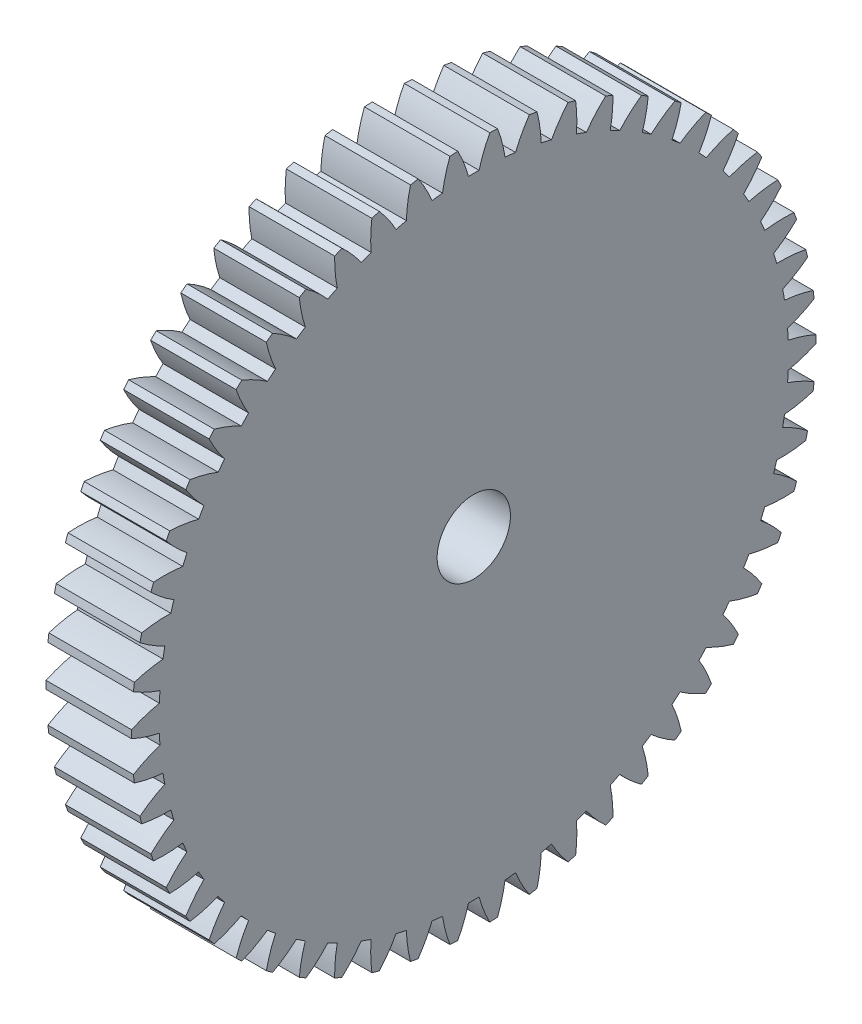
SolidWorks part; units mm, degrees
ref_plane "Plane1" through (0, 0, 0) normal (0, 0, 1) x (1, 0, 0)
ref_plane "Plane2" through (0, 0, 0) normal (0, 1, 0) x (1, 0, 0)
ref_plane "Plane3" through (0, 0, 0) normal (1, 0, 0) x (0, 0, -1)
sketch "HoldingSke" plane through (0, 0, 0) normal (0, 1, 0) x (1, 0, 0)
  line L0 (0, 0) -> (0.5878, -0.809)
  line L1 (-15, 0) -> (100, 0) construction
  line L2 (0, 0) -> (-2.1039, 2.3779)
  line L3 (0, 0) -> (-11.863, 4.5341)
  line L4 (0, 0) -> (5.0761, 6.9867)
  line L5 (0, 0) -> (-11.2434, -4.1935)
  line L6 (0, 0) -> (-5.8027, -3.9151)
  line L7 (-2.1039, 2.3779) -> (0.4791, 14.0966)
  line L8 (-76.2, 54.61) -> (-75.2, 54.61)
  line L9 (-71.009, 38.7566) -> (-53.1078, 45.2721)
  line L10 (-76.2, 71.12) -> (104.1128, 71.12)
  line L11 (0, 0) -> (-7, 0)
  line L12 (-76.2, 101.6) -> (-76.162, 101.6)
  line L13 (24.9733, 27.94) -> (52.9518, 28.4284)
  line L14 (24.9733, 27.94) -> (24.9743, 27.94)
  line L15 (24.9733, 27.94) -> (100.4006, 29.5858)
  line L16 (-63.627, -1) -> (-12.827, -1)
  circle A0 centre (0, 0) radius 3
  circle A1 centre (0, 0) radius 6
  circle A2 centre (0, 0) radius 6
  circle A3 centre (0, 0) radius 3
  dimension "MHD" = 12
  dimension "Hub_dia" = 12
  dimension "Bore" = 6
  dimension "MBD" = 6
  dimension "Num_teeth" = 54
  dimension "Pitch" = 1
  dimension "Overall_len" = 12
  dimension "Show_teeth" = 54
  dimension "Thickness" = 7
  dimension "OAL" = 12.0001
  dimension "T_dim" = 1
  dimension "Ap" = 20
  dimension "H" = 19.05
  dimension "Pitch_radius" = 180.3128
  dimension "Width" = 7
  dimension "Backlash" = 0.038
  dimension "Addendum_fac" = 1
  dimension "Dedendum_fac" = 1.25
  dimension "Clearance_fac" = 0.25
  dimension "Dedendum_add" = 0.001
  dimension "Module" = 1
sketch "BasProSke" plane through (0, 0, 0) normal (0, 1, 0) x (1, 0, 0)
  line L0 (-10, 0) -> (60, 0) construction
  line L1 (0, 0) -> (0, 28)
  line L2 (0, 0) -> (7, 0)
  line L3 (7, 0) -> (7, 28)
  line L4 (7, 28) -> (0, 28)
  dimension "Thickness" = 7
  dimension "Diameter" = 56
revolve "Base-Revolve" add sketch "BasProSke" angle 360 about L0
sketch "TooCutSke" plane through (0, 0, 0) normal (1, 0, 0) x (0, 0, -1)
  line L1 (0, 0) -> (0, 107) construction
  line L2 (0, 0) -> (-0.8518, 26.9866) construction
  line L3 (0, 0) -> (-3.1387, 53.8895) construction
  line L4 (-0.8518, 26.9866) -> (-1.5694, 26.9448) construction
  arc A0 (0.4343, 25.7453) -> (-0.4343, 25.7453) centre (0, 0) ccw
  arc A1 (1.322, 27.9942) -> (-1.322, 27.9942) centre (0, 0) ccw
  circle A2 centre (0, 0) radius 27 construction
  circle A3 centre (0, 0) radius 25.3717 construction
  arc A4 (-0.4343, 25.7453) -> (-1.322, 27.9942) centre (-10.8608, 22.9296) ccw
  arc A5 (1.322, 27.9942) -> (0.4343, 25.7453) centre (10.8608, 22.9296) ccw
  dimension "Root_dia" = 51.498
  dimension "Overcut_dia" = 56.0508
  dimension "Pitch_dia" = 54
  dimension "Base_dia" = 50.7434
  dimension "Flank_rad" = 10.8
  dimension "Half_ang" = 3.333
  dimension "Half_CT" = 0.7188
extrude "ToothCut" cut sketch "TooCutSke" along normal through all
fillet "Breaks" [suppressed] radius 0.02
fillet "RootFillets" [suppressed] radius 0.251
pattern_circular "TeethCuts" count 54 every 6.667 about axis through (-10, 0, 0) along (1, 0, 0) of "ToothCut", "RootFillets", "Breaks"
sketch "HubNeaOneSke" plane through (0, 0, 0) normal (-1, 0, 0) x (0, 0, 1)
  circle A0 centre (0, 0) radius 6
  dimension "Diameter" = 12
extrude "HubNearOne" add sketch "HubNeaOneSke" along normal blind 7
sketch "HubNeaBotSke" plane through (0, 0, 0) normal (-1, 0, 0) x (0, 0, 1)
  circle A0 centre (0, 0) radius 6
  dimension "Diameter" = 12
extrude "HubNearBoth" [suppressed] add sketch "HubNeaBotSke" along normal blind 2.5
ref_plane "FarPln" through (7, 0, 0) normal (1, 0, 0) x (0, 0, -1)
sketch "HubFarSke" plane through (7, 0, 0) normal (1, 0, 0) x (0, 0, -1)
  circle A0 centre (0, 0) radius 6
  dimension "Diameter" = 12
extrude "HubFar" [suppressed] add sketch "HubFarSke" along normal blind 2.5
sketch "BorSke" plane through (0, 0, 0) normal (1, 0, 0) x (0, 0, -1)
  circle A0 centre (0, 0) radius 3
  dimension "Diameter" = 6
extrude "Bore" cut sketch "BorSke" along normal mid plane 24.0001
sketch "KeySke" plane through (0, 0, 0) normal (1, 0, 0) x (0, 0, -1)
  line L0 (-1, 0) -> (-1, 4)
  line L1 (-1, 4) -> (1, 4)
  line L2 (1, 4) -> (1, 0)
  line L3 (0, 0) -> (0, 34) construction
  line L4 (-1, 0) -> (1, 0)
  dimension "Offset" = 4
  dimension "Width" = 2
extrude "Keyway" [suppressed] cut sketch "KeySke" along normal mid plane 24.0001
pattern_circular "Keyway2" [suppressed] count 2 every 90 about axis through (-10, 0, 0) along (1, 0, 0)
hole_wizard "Trou pour taraudage pour trou taraudé M3x0.51" positions "Esquisse3D1" profile "Esquisse1" hole size "M3x0.5" standard "Ansi Metric"
sketch3d "Esquisse3D1"
  point P0 (-3.5, -1.3572, -5.8445)
  dimension "D1" = 3.5
sketch "Esquisse1" plane through (-3.5, -1.3572, -5.8445) normal (1, 0, 0) x (0, 0.9741, -0.2262)
  line L0 (0, 0) -> (0, 5.7511)
  line L1 (0, 5.7511) -> (1.25, 5)
  line L2 (1.25, 5) -> (1.25, 0)
  line L5 (1.25, 0) -> (0, 0)
  line L10 (0, 5.7511) -> (-1.25, 5) construction
  line L11 (0, -6.35) -> (0, 107.95) construction
  dimension "Diamètre du perçage" = 2.5
  dimension "Profondeur du perçage" = 5
  dimension "Angle de pointe" = 118
pattern_circular "Répétition circulaire1" count 2 every 90 about axis through (12.0001, 0, 0) along (-1, 0, 0) of "Trou pour taraudage pour trou taraudé M3x0.51"
equation "' \"Module@HoldingSke\" = 6.35"
equation "' \"Num_teeth@HoldingSke\" = 12"
equation "' \"Ap@HoldingSke\" =  20"
equation "' \"Ap@HoldingSke\" = 20"
equation "' \"Width@HoldingSke\" = 0.5 * 25.4"
equation "' \"Hub_dia@HoldingSke\"= 1 * 25.4"
equation "' \"Hub_dia@HoldingSke\" = 1 * 25.4"
equation "' \"Overall_len@HoldingSke\" = 1.0 * 25.4"
equation "' \"Bore@HoldingSke\" = 0.75 * 25.4"
equation "' \"T_dim@HoldingSke\" = 0.1 * 25.4"
equation "' \"Width@KeySke\" = 0.25 * 25.4"
equation "' \"Show_teeth@HoldingSke\" = 13"
equation "' \"Backlash@HoldingSke\" = 0.009 * 25.4"
equation "' \"Addendum_fac@HoldingSke\" = 1.0"
equation "' \"Dedendum_fac@HoldingSke\" = 1.25"
equation "' \"Dedendum_add@HoldingSke\" = 0.00005 * 25.4"
equation "' \"Clearance_fac@HoldingSke\" = 0.25"
equation "\"Pitch@HoldingSke\" = 1 / \"Module@HoldingSke\""
equation "\"Overcut_dia@TooCutSke\" = (\"Num_teeth@HoldingSke\" + 2 * \"Addendum_fac@HoldingSke\") / \"Pitch@HoldingSke\" + 0.002 * 25.4"
equation "\"Pitch_dia@TooCutSke\" = \"Num_teeth@HoldingSke\" / \"Pitch@HoldingSke\""
equation "\"Base_dia@TooCutSke\" = \"Num_teeth@HoldingSke\" / \"Pitch@HoldingSke\" * cos((\"Ap@HoldingSke\"  * 3.14159265 / 180))"
equation "\"Root_dia@TooCutSke\" = (\"Num_teeth@HoldingSke\" + 2) / \"Pitch@HoldingSke\" - 2 * (\"Addendum_fac@HoldingSke\" + \"Dedendum_fac@HoldingSke\") / \"Pitch@HoldingSke\" - \"Dedendum_add@HoldingSke\" * 2"
equation "\"Half_ang@TooCutSke\" = 180 / \"Num_teeth@HoldingSke\""
equation "\"Half_CT@TooCutSke\" = \"Num_teeth@HoldingSke\" / \"Pitch@HoldingSke\" * sin((3.14159265 / 2 / \"Num_teeth@HoldingSke\")) / 2 - 7 * \"Backlash@HoldingSke\" / 4"
equation "\"Flank_rad@TooCutSke\" = \"Num_teeth@HoldingSke\" / \"Pitch@HoldingSke\" / 5"
equation "\"Radius@RootFillets\" = \"Clearance_fac@HoldingSke\" / \"Pitch@HoldingSke\" + \"Dedendum_add@HoldingSke\""
equation "\"Break_rad@Breaks\" = 0.02 / \"Pitch@HoldingSke\""
equation "\"Thickness@HoldingSke\" = \"Width@HoldingSke\""
equation "\"OAL@HoldingSke\" = \"Thickness@HoldingSke\""
equation "\"MHD@HoldingSke\" = (\"Num_teeth@HoldingSke\" + 2) / \"Pitch@HoldingSke\" - 2 * (\"Addendum_fac@HoldingSke\" + \"Dedendum_fac@HoldingSke\")  / \"Pitch@HoldingSke\" - \"Dedendum_add@HoldingSke\" * 2"
equation "\"MBD@HoldingSke\" = (\"Num_teeth@HoldingSke\" + 2) / \"Pitch@HoldingSke\" - 2 * (\"Addendum_fac@HoldingSke\" + \"Dedendum_fac@HoldingSke\")  / \"Pitch@HoldingSke\" - \"Dedendum_add@HoldingSke\" * 2 - 0.002 * 25.4"
equation "\"MHD@HoldingSke\" = ((sgn( \"MHD@HoldingSke\" - \"Hub_dia@HoldingSke\" )-1)*( \"MHD@HoldingSke\" - \"Hub_dia@HoldingSke\" ))/-2+ \"Hub_dia@HoldingSke\""
equation "\"MBD@HoldingSke\" = ((sgn( \"MBD@HoldingSke\" - \"Bore@HoldingSke\" )-1)*( \"MBD@HoldingSke\" - \"Bore@HoldingSke\" ))/-2+ \"Bore@HoldingSke\""
equation "\"OAL@HoldingSke\" = ((sgn( \"OAL@HoldingSke\" - \"Overall_len@HoldingSke\" )+1)*( \"OAL@HoldingSke\" - \"Overall_len@HoldingSke\" ))/2 + \"Overall_len@HoldingSke\" + 0.000002 * 25.4"
equation "\"Num_teeth@TeethCuts\" = int( \"Show_teeth@HoldingSke\" ) + 1"
equation "\"Num_teeth@TeethCuts\" = ((sgn( \"Num_teeth@TeethCuts\" - \"Num_teeth@HoldingSke\" )-1)*( \"Num_teeth@TeethCuts\" - \"Num_teeth@HoldingSke\" ))/-2+ \"Num_teeth@HoldingSke\""
equation "\"Num_teeth@TeethCuts\" = ((sgn( \"Num_teeth@TeethCuts\" - 2.0)+1)*( \"Num_teeth@TeethCuts\" - 2.0))/2 +2.0"
equation "\"Angle@TeethCuts\" = 360.0 / \"Num_teeth@HoldingSke\""
equation "\"Diameter@BasProSke\" = (\"Num_teeth@HoldingSke\" + 2 * \"Addendum_fac@HoldingSke\") / \"Pitch@HoldingSke\""
equation "\"Thickness@BasProSke\"  = \"Thickness@HoldingSke\""
equation "' \"Fillet_rad@BasProSke\" =  \"Thickness@HoldingSke\" * 0.05"
equation "' \"Fillet_rad@BasProSke\" = \"Thickness@HoldingSke\" * 0.05"
equation "\"MHD@HoldingSke\" = ((sgn( \"MHD@HoldingSke\" - \"Root_dia@TooCutSke\" )-1)*( \"MHD@HoldingSke\" - \"Root_dia@TooCutSke\" ))/-2+ \"Root_dia@TooCutSke\""
equation "\"Diameter@HubNeaOneSke\" = \"MHD@HoldingSke\""
equation "\"Diameter@HubNeaBotSke\" = \"MHD@HoldingSke\""
equation "\"Length@HubNearBoth\" = ( \"OAL@HoldingSke\" - \"Thickness@BasProSke\" ) / 2.0"
equation "\"Thickness@FarPln\" = \"Thickness@BasProSke\""
equation "\"Diameter@HubFarSke\" = \"MHD@HoldingSke\""
equation "\"Length@HubFar\" = ( \"OAL@HoldingSke\" - \"Thickness@BasProSke\" ) / 2.0"
equation "\"Diameter@BorSke\" = \"MBD@HoldingSke\""
equation "\"D1@Bore\" = \"OAL@HoldingSke\" * 2.0"
equation "\"D1@Keyway\" = \"OAL@HoldingSke\" * 2.0"
equation "\"Offset@KeySke\" = \"T_dim@HoldingSke\" + \"MBD@HoldingSke\" / 2.0"
